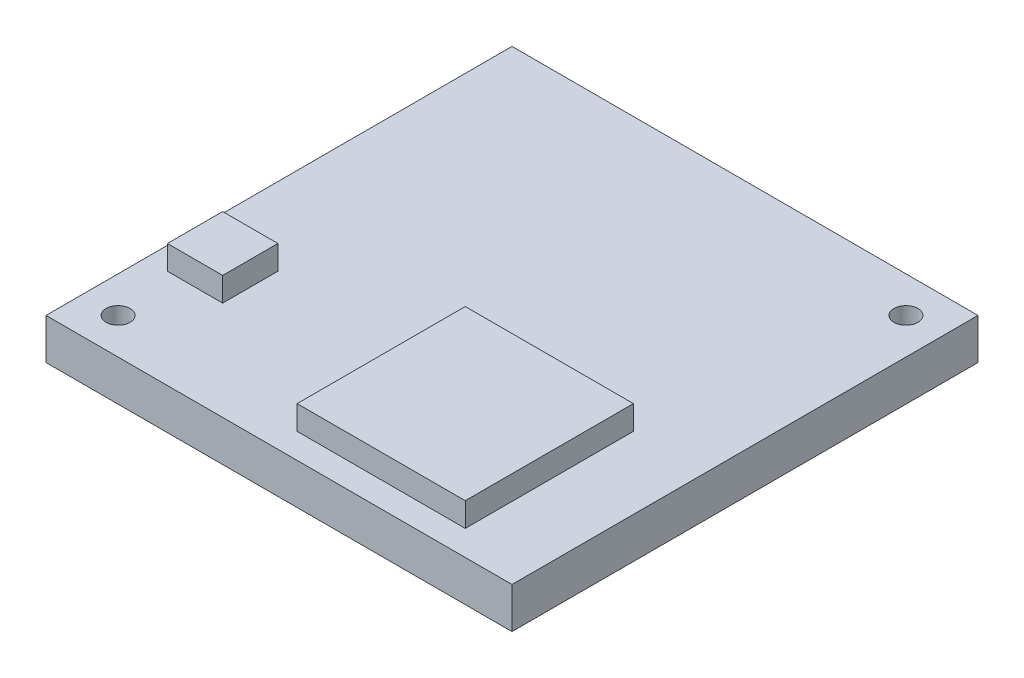
SolidWorks part; units mm, degrees
ref_plane "Front Plane" through (0, 0, 0) normal (0, 0, 1) x (1, 0, 0)
ref_plane "Top Plane" through (0, 0, 0) normal (0, 1, 0) x (1, 0, 0)
ref_plane "Right Plane" through (0, 0, 0) normal (1, 0, 0) x (0, 0, -1)
sketch "Sketch1" plane through (0, 0, 0) normal (0, 1, 0) x (1, 0, 0)
  line L1 (9.7, -9.7) -> (-9.7, -9.7)
  line L2 (9.7, -9.7) -> (9.7, 9.7)
  line L3 (9.7, 9.7) -> (-9.7, 9.7)
  line L4 (-9.7, -9.7) -> (-9.7, 9.7)
  line L5 (9.7, -9.7) -> (-9.7, 9.7) construction
  line L6 (9.7, 9.7) -> (-9.7, -9.7) construction
  circle A0 centre (-8.2, -8.2) radius 0.5
  circle A1 centre (8.2, 8.2) radius 0.5
  point P0 (0, 0)
  dimension "D5" = 1
  dimension "D6" = 1
  dimension "D1" = 19.4
  dimension "D2" = 19.4
  dimension "D3" = 1.5
  dimension "D4" = 1.5
extrude "Boss-Extrude1" add sketch "Sketch1" along normal blind 1.7
sketch "Sketch2" plane through (0, 1.7, 0) normal (0, 1, 0) x (1, 0, 0)
  line L1 (-0.2939, -1.6519) -> (6.7061, -1.6519)
  line L2 (-0.2939, -1.6519) -> (-0.2939, -8.6519)
  line L3 (-0.2939, -8.6519) -> (6.7061, -8.6519)
  line L4 (6.7061, -1.6519) -> (6.7061, -8.6519)
  line L5 (-0.2939, -1.6519) -> (6.7061, -8.6519) construction
  line L6 (-0.2939, -8.6519) -> (6.7061, -1.6519) construction
  line L7 (-8.7667, -3.2792) -> (-6.4667, -3.2792)
  line L8 (-8.7667, -3.2792) -> (-8.7667, -5.5792)
  line L9 (-8.7667, -5.5792) -> (-6.4667, -5.5792)
  line L10 (-6.4667, -3.2792) -> (-6.4667, -5.5792)
  line L11 (-8.7667, -3.2792) -> (-6.4667, -5.5792) construction
  line L12 (-8.7667, -5.5792) -> (-6.4667, -3.2792) construction
  point P0 (3.2061, -5.1519)
  point P5 (-7.6167, -4.4292)
  point P6 (-7.6167, -4.4292)
  dimension "D1" = 7
  dimension "D2" = 7
  dimension "D3" = 2.3
  dimension "D4" = 2.3
extrude "Boss-Extrude2" add sketch "Sketch2" along normal blind 1
